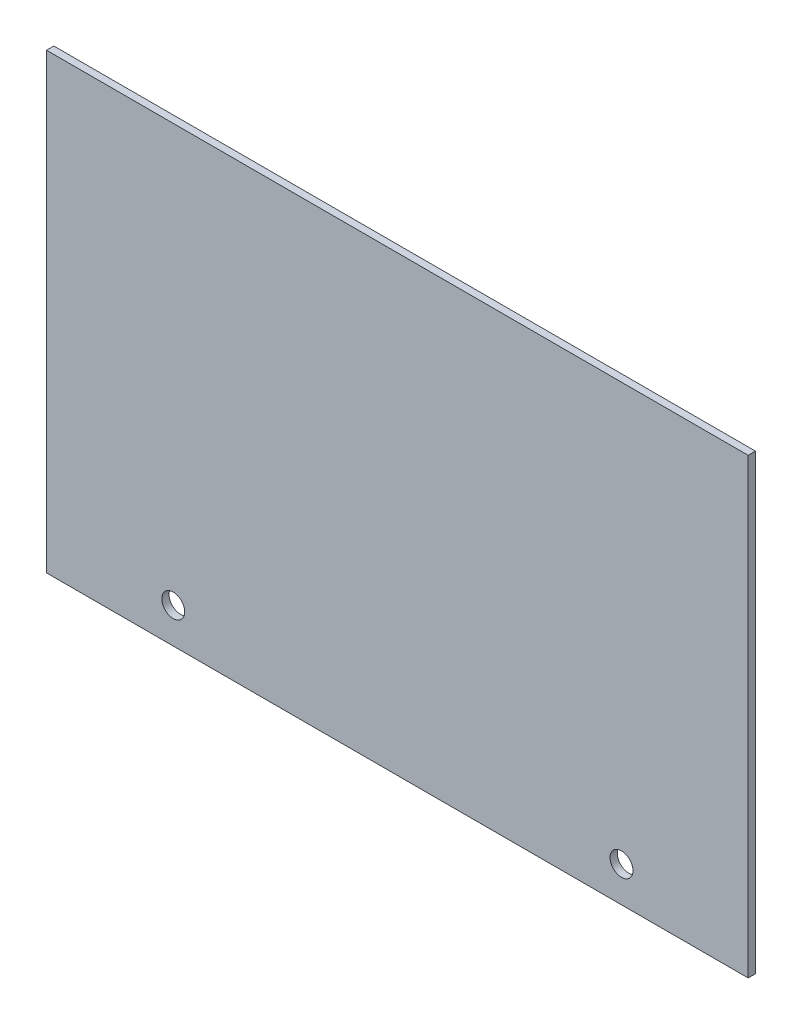
SolidWorks part; units mm, degrees
material "ABS"
ref_plane "X-Y Datum" through (0, 0, 0) normal (0, 0, 1) x (1, 0, 0)
ref_plane "X-Z Datum" through (0, 0, 0) normal (0, 1, 0) x (1, 0, 0)
ref_plane "Y-Z Datum" through (0, 0, 0) normal (1, 0, 0) x (0, 0, -1)
sketch "Sketch1" plane through (0, 0, 0) normal (0, 0, 1) x (1, 0, 0)
  line L0 (-153.025, 98.7125) -> (-153.025, -98.7125)
  line L1 (-153.025, 98.7125) -> (153.025, 98.7125)
  line L2 (-153.025, 98.7125) -> (-153.025, -98.7125)
  line L3 (-153.025, -98.7125) -> (153.025, -98.7125)
  line L4 (153.025, 98.7125) -> (153.025, -98.7125)
  line L5 (-153.025, 98.7125) -> (153.025, -98.7125) construction
  line L6 (-153.025, -98.7125) -> (153.025, 98.7125) construction
  line L7 (-153.025, -98.7125) -> (153.025, -98.7125)
  line L8 (153.025, 98.7125) -> (153.025, -98.7125)
  line L9 (-153.025, 98.7125) -> (153.025, 98.7125)
  circle A0 centre (-142.25, -87.9375) radius 10.775
  circle A1 centre (-118.25, -87.9375) radius 10.775 construction
  circle A2 centre (-130.25, -64.9375) radius 10.775
  point P0 (0, 0)
  dimension "D1" = 21.55
  dimension "D2" = 24
  dimension "D3" = 23
  dimension "D4" = 12
  dimension "D5" = 197.425
  dimension "D6" = 306.05
  dimension "D7" = 0
extrude "Boss-Extrude1" add sketch "Sketch1" along normal blind 3.175 contours A0 L3 L4 L1 L2 A2 | A2 | A0 | A0 L2 L3 | L9 L0 L7 L8 L1 L4 L3 L2
sketch "Sketch2" plane through (0, 0, 0) normal (0, 0, -1) x (-1, 0, 0)
  circle A1 centre (-97.75, -83.334) radius 5
  circle A2 centre (-97.75, -83.334) radius 5
  dimension "D1" = 0
extrude "Cut-Extrude1" cut sketch "Sketch2" against normal through all
mirror "Mirror1" about plane through (0, 0, 0) normal (1, 0, 0) of "Cut-Extrude1"
